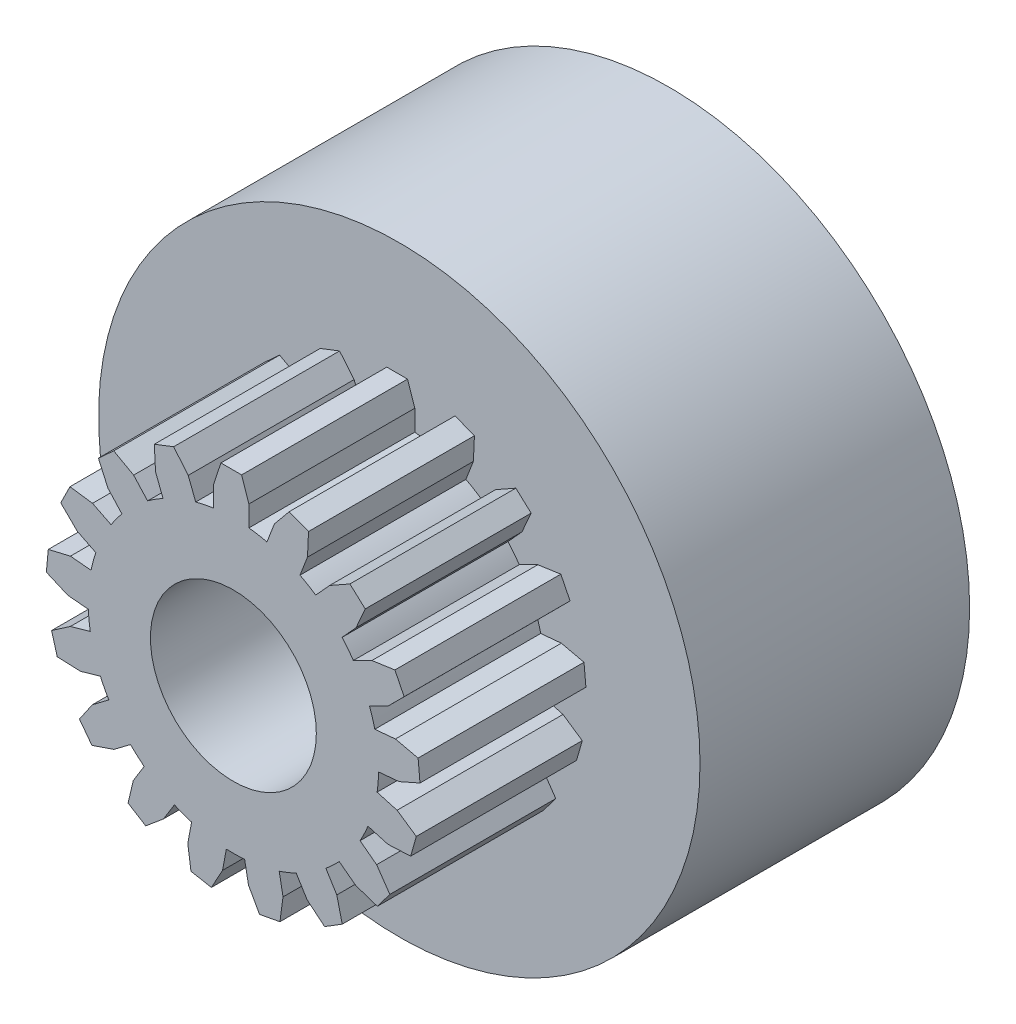
SolidWorks part; units mm, degrees
material "Cast Alloy Steel"
ref_plane "Front" through (0, 0, 0) normal (0, 0, 1) x (1, 0, 0)
ref_plane "Top" through (0, 0, 0) normal (0, 1, 0) x (1, 0, 0)
ref_plane "Right" through (0, 0, 0) normal (1, 0, 0) x (0, 0, -1)
sketch "Sketch2" plane through (0, 0, 0) normal (0, 0, 1) x (1, 0, 0)
  circle A0 centre (0, 0) radius 7
extrude "Boss-Extrude1" add sketch "Sketch2" along normal blind 8
sketch "Sketch4" plane through (0, 0, 0) normal (0, 0, 1) x (1, 0, 0)
  line L0 (-0.9518, 7) -> (0.7482, 7) construction
  line L1 (-0.9518, 6.935) -> (-0.9518, 7.935)
  line L2 (0.7482, 6.9599) -> (0.7482, 7.9599)
  line L3 (-0.1018, 9) -> (-0.1018, 7) construction
  line L4 (-0.6018, 9) -> (0.3982, 9)
  line L5 (0.3982, 9) -> (0.7482, 7.9599)
  line L6 (-0.6018, 9) -> (-0.9518, 7.935)
  circle A0 centre (0, 0) radius 7 construction
  arc A1 (-0.9518, 6.935) -> (0.7482, 6.9599) centre (0, 0) cw
  dimension "D1" = 1.7
  dimension "D2" = 2
  dimension "D3" = 0.5
  dimension "D4" = 0.5
extrude "Boss-Extrude2" add sketch "Sketch4" along normal blind 8 contours L1 A1 L2 L5 L4 L6
pattern_circular "CirPattern1" count 17 over 360 about axis through (0, 0, 0) along (0, 0, 1) of "Boss-Extrude2"
sketch "Sketch5" plane through (0, 0, 0) normal (0, 0, -1) x (-1, 0, 0)
  circle A0 centre (0, 0) radius 14.5
extrude "Boss-Extrude3" add sketch "Sketch5" along normal blind 13
sketch "Sketch6" plane through (0, 0, -13) normal (0, 0, -1) x (-1, 0, 0)
  circle A0 centre (0, 0) radius 13.5
extrude "Cut-Extrude1" cut sketch "Sketch6" against normal blind 11
sketch "Sketch7" plane through (0, 0, 8) normal (0, 0, 1) x (1, 0, 0)
  circle A0 centre (0, 0) radius 4
extrude "Cut-Extrude2" cut sketch "Sketch7" against normal blind 11
